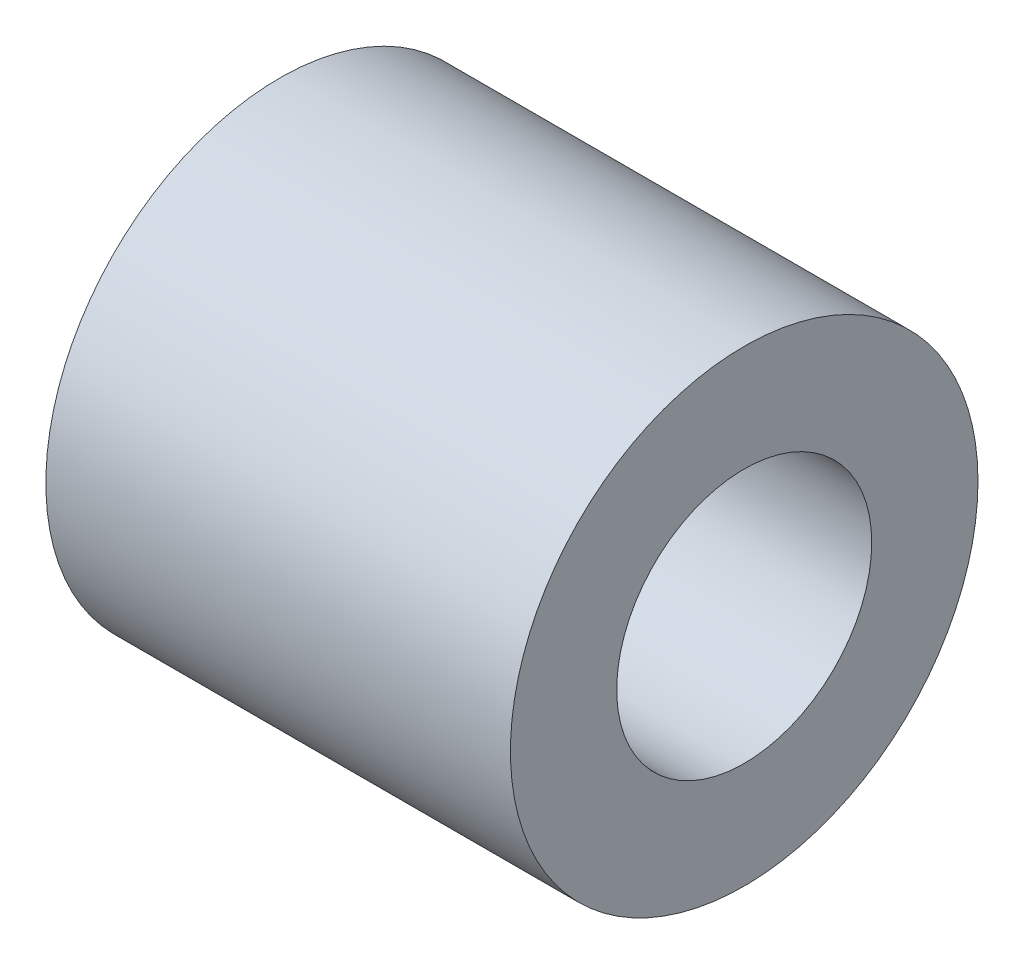
SolidWorks part; units mm, degrees
ref_plane "前视基准面" through (0, 0, 0) normal (0, 0, 1) x (1, 0, 0)
ref_plane "上视基准面" through (0, 0, 0) normal (0, 1, 0) x (1, 0, 0)
ref_plane "右视基准面" through (0, 0, 0) normal (1, 0, 0) x (0, 0, -1)
sketch "草图1" plane through (0, 0, 0) normal (1, 0, 0) x (0, 0, -1)
  circle A0 centre (0, 0) radius 3
  circle A1 centre (0, 0) radius 5.5
extrude "凸台-拉伸1" add sketch "草图1" along normal blind 10.93
